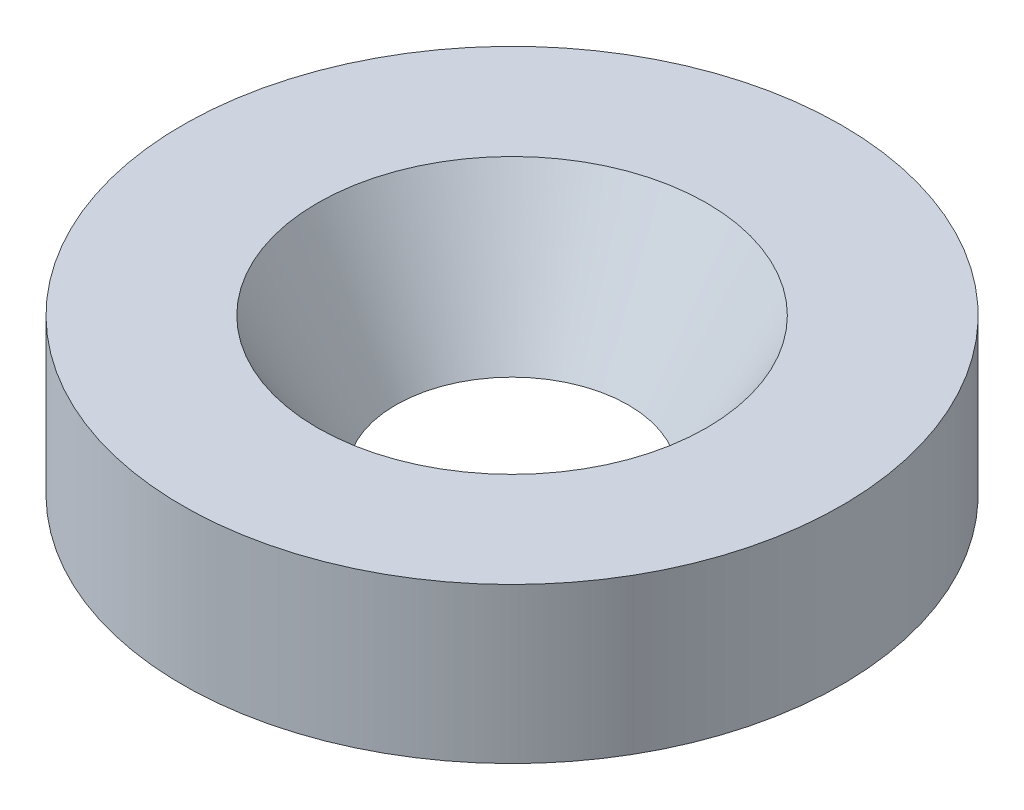
SolidWorks part; units mm, degrees
ref_plane "Plano frontal" through (0, 0, 0) normal (0, 0, 1) x (1, 0, 0)
ref_plane "Plano superior" through (0, 0, 0) normal (0, 1, 0) x (1, 0, 0)
ref_plane "Plano direito" through (0, 0, 0) normal (1, 0, 0) x (0, 0, -1)
sketch "Sketch1" plane through (0, 0, 0) normal (1, 0, 0) x (0, 0, -1)
  line L0 (0, 0) -> (0, 10.5227) construction
  line L1 (8, 0) -> (8.5, 0)
  line L2 (8.5, 0) -> (8.5, 4)
  line L3 (8.5, 4) -> (5.0207, 4)
  line L4 (5.0207, 4) -> (3, 0.5)
  line L5 (3, 0.5) -> (6, 0.5)
  line L6 (6, 0.5) -> (6, 2.75)
  line L7 (6, 2.75) -> (8, 2.75)
  line L8 (8, 2.75) -> (8, 0)
  dimension "D1" = 8.5
  dimension "D2" = 0.5
  dimension "D3" = 4
  dimension "D4" = 2
  dimension "D5" = 3
  dimension "D6" = 2.25
  dimension "D7" = 1.25
  dimension "D8" = 60
revolve "Revolve1" add sketch "Sketch1" angle 360 about L0
